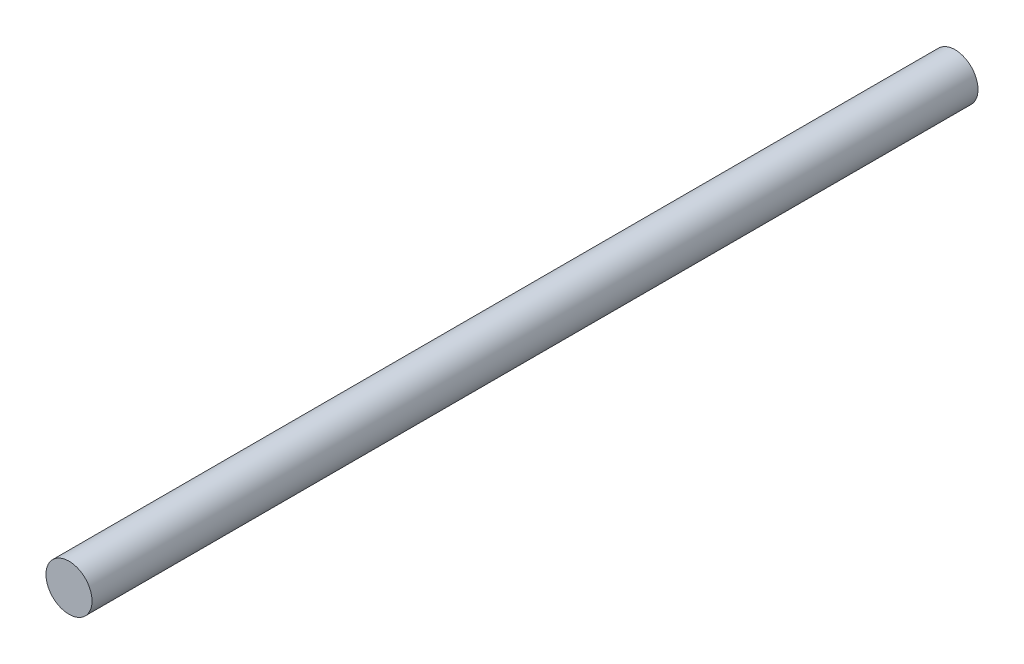
SolidWorks part; units mm, degrees
material "PW50:3:C1:0:1:2:Re:26:"
ref_plane "Plane1" through (0, 0, 0) normal (0, 0, 1) x (1, 0, 0)
ref_plane "Plane2" through (0, 0, 0) normal (0, 1, 0) x (1, 0, 0)
ref_plane "Plane3" through (0, 0, 0) normal (1, 0, 0) x (0, 0, -1)
other "Configuration Table"
sketch "Sketch1" plane through (0, 0, 0) normal (0, 0, 1) x (1, 0, 0)
  circle A0 centre (-86.9967, -495.5788) radius 3.25 construction
  circle A1 centre (-86.9967, -495.5788) radius 3.25
extrude "Base-Extrude" add sketch "Sketch1" along normal blind 125
